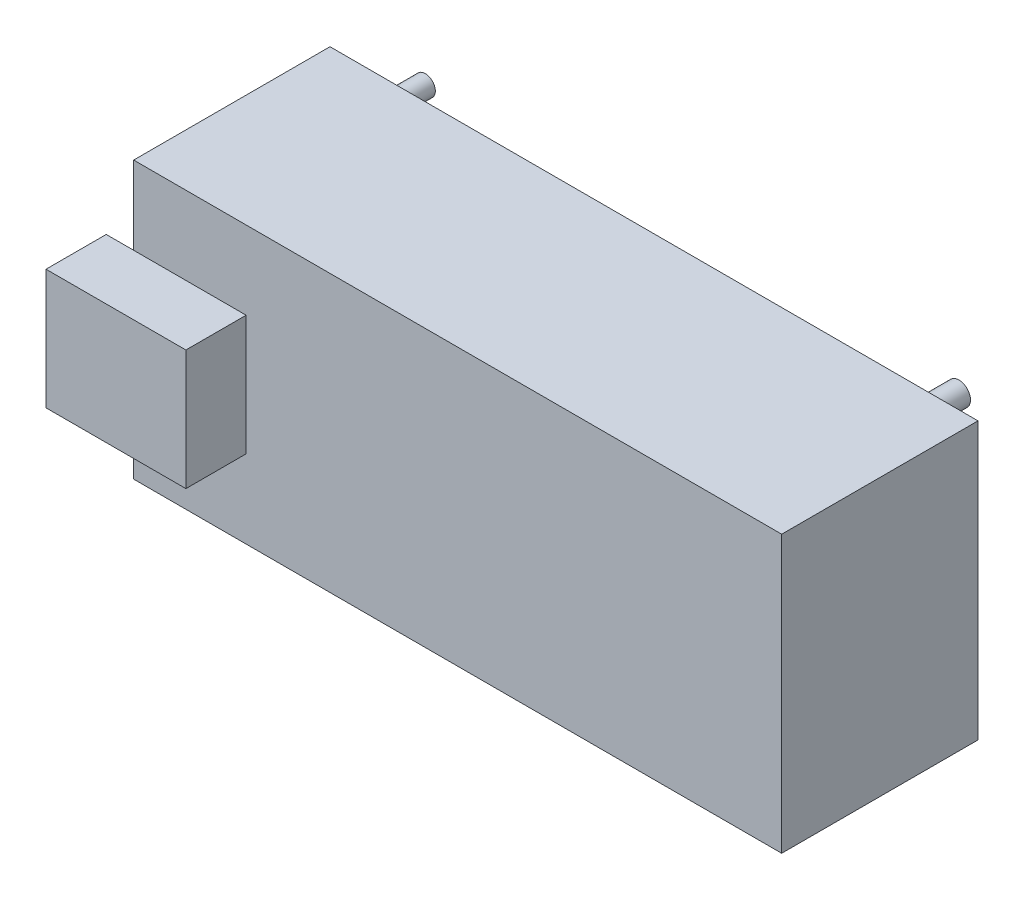
SolidWorks part; units mm, degrees
ref_plane "Front Plane" through (0, 0, 0) normal (0, 0, 1) x (1, 0, 0)
ref_plane "Top Plane" through (0, 0, 0) normal (0, 1, 0) x (1, 0, 0)
ref_plane "Right Plane" through (0, 0, 0) normal (1, 0, 0) x (0, 0, -1)
sketch "Sketch1" plane through (0, 0, 0) normal (0, 0, 1) x (1, 0, 0)
  line L1 (21.59, 9.2075) -> (-21.59, 9.2075)
  line L2 (21.59, 9.2075) -> (21.59, -9.2075)
  line L3 (21.59, -9.2075) -> (-21.59, -9.2075)
  line L4 (-21.59, 9.2075) -> (-21.59, -9.2075)
  line L5 (21.59, 9.2075) -> (-21.59, -9.2075) construction
  line L6 (21.59, -9.2075) -> (-21.59, 9.2075) construction
  point P0 (0, 0)
  dimension "D1" = 43.18
  dimension "D2" = 18.415
extrude "Extrude1" add sketch "Sketch1" along normal blind 13.081
sketch "Sketch2" plane through (0, 0, 0) normal (0, 0, -1) x (-1, 0, 0)
  line L0 (0, 9.2075) -> (0, -9.2075) construction
  line L1 (-21.59, 9.2075) -> (21.59, 9.2075) construction
  line L2 (21.59, -9.2075) -> (-21.59, -9.2075) construction
  line L3 (-21.59, 0) -> (21.59, 0) construction
  line L4 (-21.59, -9.2075) -> (-21.59, 9.2075) construction
  line L5 (21.59, 9.2075) -> (21.59, -9.2075) construction
  circle A0 centre (-17.78, 7.62) radius 0.7699
  circle A1 centre (-17.78, -7.62) radius 0.7216
  circle A2 centre (17.78, -7.62) radius 0.7621
  circle A3 centre (17.78, 7.62) radius 0.6713
  dimension "D1" = 35.56
  dimension "D2" = 15.24
extrude "Extrude2" add sketch "Sketch2" along normal blind 2.54
sketch "Sketch4" plane through (0, 0, 13.081) normal (0, 0, 1) x (1, 0, 0)
  line L0 (-21.59, 0) -> (21.59, 0) construction
  line L1 (-14.097, 4.0005) -> (-23.4188, 4.0005)
  line L2 (-14.097, 4.0005) -> (-14.097, -4.0005)
  line L3 (-14.097, -4.0005) -> (-23.4188, -4.0005)
  line L4 (-23.4188, 4.0005) -> (-23.4188, -4.0005)
  line L5 (-21.59, 9.2075) -> (-21.59, -9.2075) construction
  line L6 (21.59, -9.2075) -> (21.59, 9.2075) construction
  dimension "D1" = 8.001
  dimension "D2" = 9.3218
  dimension "D3" = 1.8288
extrude "Extrude3" add sketch "Sketch4" along normal blind 4.0132
